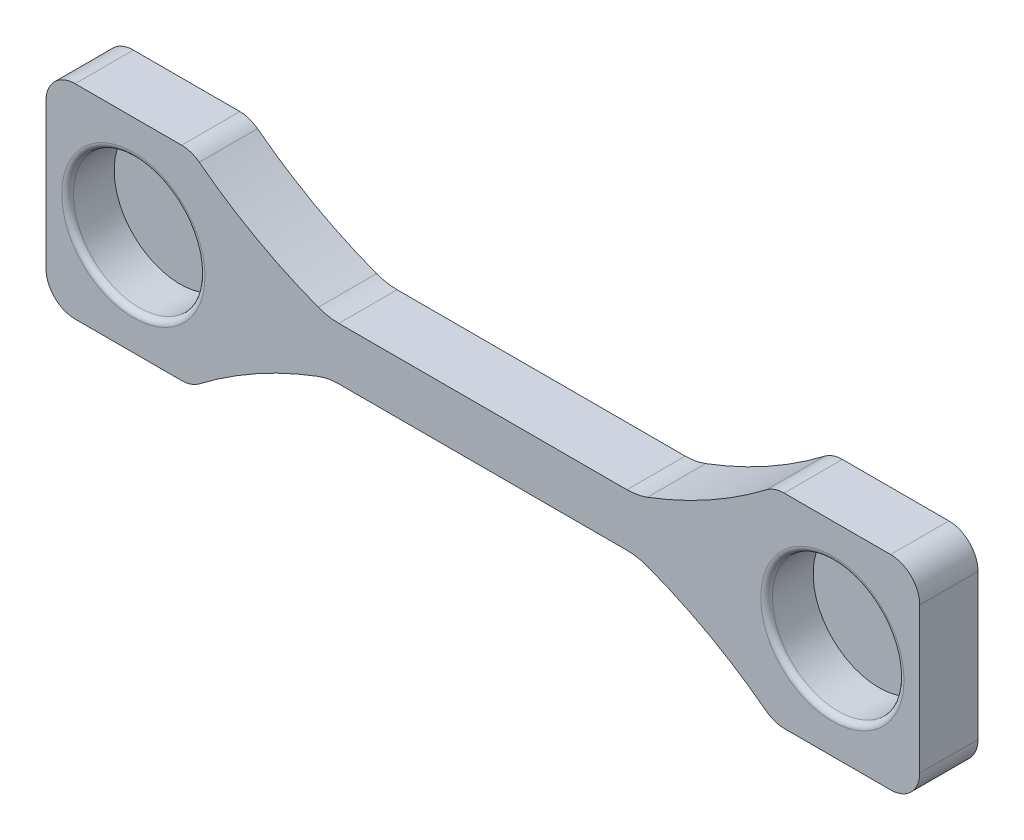
SolidWorks part; units mm, degrees
ref_plane "Front" through (0, 0, 0) normal (0, 0, 1) x (1, 0, 0)
ref_plane "Top" through (0, 0, 0) normal (0, 1, 0) x (1, 0, 0)
ref_plane "Right" through (0, 0, 0) normal (1, 0, 0) x (0, 0, -1)
sketch "Sketch1" plane through (0, 0, 0) normal (0, 0, 1) x (1, 0, 0)
  line L1 (75, -17.5) -> (-75, -17.5)
  line L2 (75, -17.5) -> (75, 17.5)
  line L3 (75, 17.5) -> (-75, 17.5)
  line L4 (-75, -17.5) -> (-75, 17.5)
  line L5 (75, -17.5) -> (-75, 17.5) construction
  line L6 (75, 17.5) -> (-75, -17.5) construction
  point P0 (0, 0)
  dimension "D1" = 150
  dimension "D2" = 35
extrude "Boss-Extrude1" add sketch "Sketch1" along normal blind 10
sketch "Sketch2" plane through (0, 0, 10) normal (0, 0, 1) x (1, 0, 0)
  line L0 (-75, 17.5) -> (-75, -17.5) construction
  line L1 (75, -17.5) -> (75, 17.5) construction
  circle A0 centre (-60, 0) radius 11.3
  circle A1 centre (60, 0) radius 11.3
  dimension "D1" = 22.6
  dimension "D2" = 15
  dimension "D3" = 15
extrude "Cut-Extrude1" cut sketch "Sketch2" against normal blind 8
sketch "Sketch3" plane through (0, 0, 10) normal (0, 0, 1) x (1, 0, 0)
  line L0 (0, 0) -> (8.3043, 0)
  line L1 (75, 17.5) -> (-75, 17.5) construction
  line L2 (-24.7292, 4.5014) -> (24.7292, 4.5014)
  line L3 (-24.7292, -4.5014) -> (24.7292, -4.5014)
  line L4 (-50, 17.5) -> (50, 17.5)
  line L5 (-50, -17.5) -> (50, -17.5)
  arc A0 (-28.253, 5.1428) -> (-50, 17.5) centre (0, 80.1786) cw
  arc A1 (28.253, 5.1428) -> (50, 17.5) centre (0, 80.1786) ccw
  arc A2 (-24.7292, 4.5014) -> (-28.253, 5.1428) centre (-24.7292, 14.5014) cw
  arc A3 (28.253, 5.1428) -> (24.7292, 4.5014) centre (24.7292, 14.5014) cw
  arc A4 (28.253, -5.1428) -> (24.7292, -4.5014) centre (24.7292, -14.5014) ccw
  arc A5 (28.253, -5.1428) -> (50, -17.5) centre (0, -80.1786) cw
  arc A6 (-24.7292, -4.5014) -> (-28.253, -5.1428) centre (-24.7292, -14.5014) ccw
  arc A7 (-28.253, -5.1428) -> (-50, -17.5) centre (0, -80.1786) ccw
  line M4 (-75, -17.5) -> (75, -17.5)
  line M6 (75, 17.5) -> (-75, 17.5)
  dimension "D1" = 10
  dimension "D2" = 10
extrude "Cut-Extrude2" cut sketch "Sketch3" against normal through all contours A6 A7 A5 A4 L3 M4 | A3 A1 A0 A2 L2 M6
fillet "Fillet1" radius 5 8 edges at (-50, 17.5, 5) (-50, -17.5, 5) (50, -17.5, 5) (50, 17.5, 5) (75, 17.5, 5) (75, -17.5, 5) (-75, 17.5, 5) (-75, -17.5, 5)
fillet "Fillet2" radius 1 2 edges at (71.3, 0, 10) (-48.7, 0, 10)
